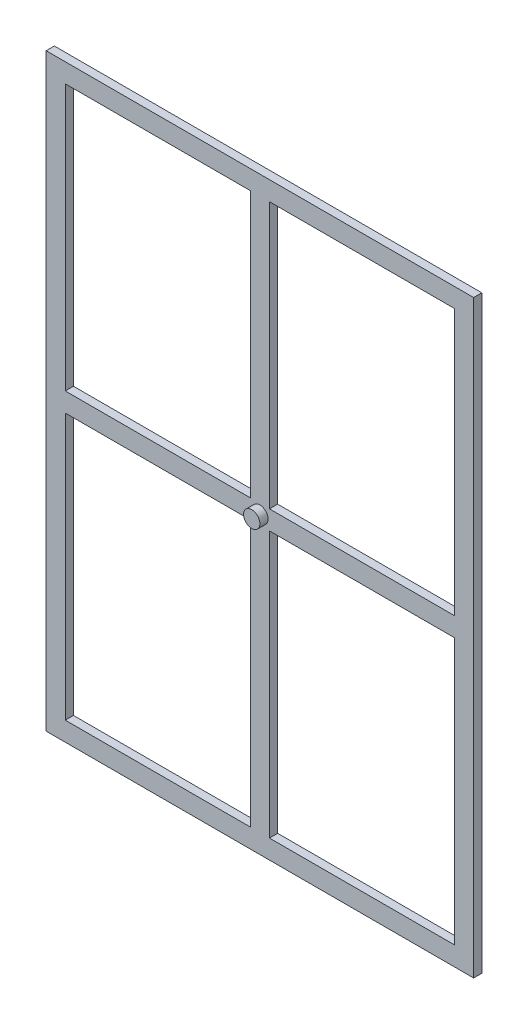
SolidWorks part; units mm, degrees
ref_plane "Plano frontal" through (0, 0, 0) normal (0, 0, 1) x (1, 0, 0)
ref_plane "Plano superior" through (0, 0, 0) normal (0, 1, 0) x (1, 0, 0)
ref_plane "Plano direito" through (0, 0, 0) normal (1, 0, 0) x (0, 0, -1)
sketch "Esboço1" plane through (0, 0, 0) normal (0, 0, 1) x (1, 0, 0)
  line L0 (-78.34, 108) -> (78.34, 108)
  line L1 (-78.34, 108) -> (-78.34, -108)
  line L2 (-78.34, -108) -> (78.34, -108)
  line L3 (78.34, 108) -> (78.34, -108)
  line L4 (-71.34, 101) -> (-3.5, 101)
  line L5 (-71.34, 101) -> (-71.34, 3.5)
  line L6 (-71.34, 3.5) -> (-3.5, 3.5)
  line L7 (-3.5, 101) -> (-3.5, 3.5)
  line L8 (3.5, 101) -> (71.34, 101)
  line L9 (3.5, 101) -> (3.5, 3.5)
  line L10 (3.5, 3.5) -> (71.34, 3.5)
  line L11 (71.34, 101) -> (71.34, 3.5)
  line L12 (-71.34, -3.5) -> (-3.5, -3.5)
  line L13 (-71.34, -3.5) -> (-71.34, -101)
  line L14 (-71.34, -101) -> (-3.5, -101)
  line L15 (-3.5, -3.5) -> (-3.5, -101)
  line L16 (3.5, -3.5) -> (71.34, -3.5)
  line L17 (3.5, -3.5) -> (3.5, -101)
  line L18 (3.5, -101) -> (71.34, -101)
  line L19 (71.34, -3.5) -> (71.34, -101)
  dimension "D1" = 156.68
extrude "Ressalto-extrusão1" add sketch "Esboço1" along normal blind 3
sketch "Esboço2" plane through (0, 0, 3) normal (0, 0, 1) x (1, 0, 0)
  circle A0 centre (0, 0) radius 3
extrude "Ressalto-extrusão2" add sketch "Esboço2" along normal blind 3
sketch "Esboço3" plane through (0, 0, 0) normal (0, 0, -1) x (-1, 0, 0)
  circle A0 centre (-74.34, 104) radius 2
  circle A1 centre (74.34, 104) radius 2
  circle A2 centre (74.34, -104) radius 2
  circle A3 centre (-74.34, -104) radius 2
extrude "Corte-extrusão1" cut sketch "Esboço3" against normal blind 1
